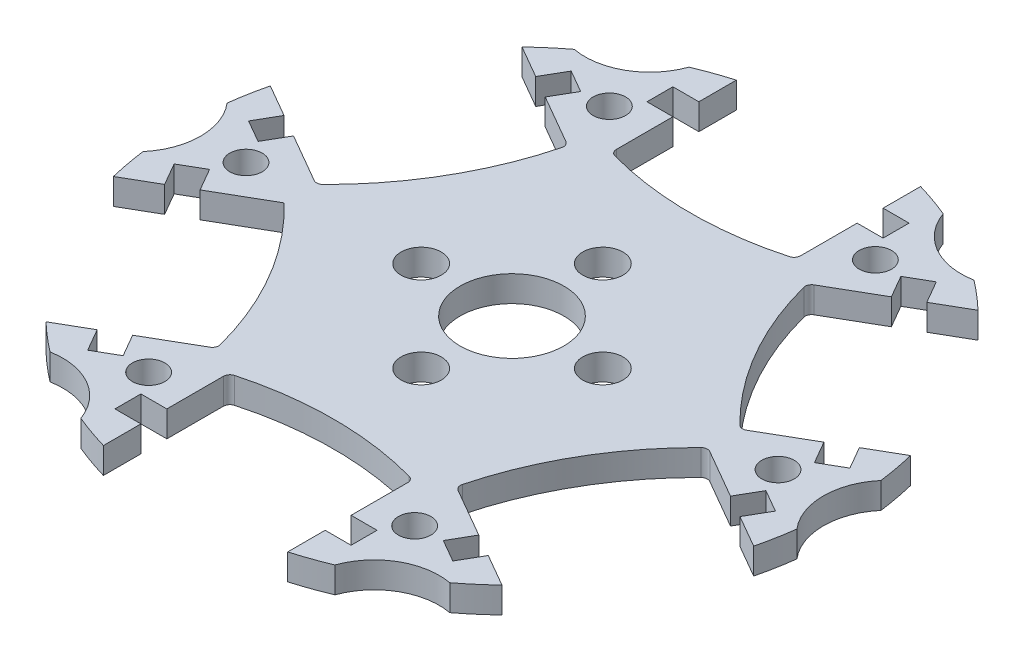
SolidWorks part; units mm, degrees
material "Hexcel AS4C (3000 丝)"
ref_plane "前视基准面" through (0, 0, 0) normal (0, 0, 1) x (1, 0, 0)
ref_plane "上视基准面" through (0, 0, 0) normal (0, 1, 0) x (1, 0, 0)
ref_plane "右视基准面" through (0, 0, 0) normal (1, 0, 0) x (0, 0, -1)
sketch "草图1" plane through (0, 0, 0) normal (0, 1, 0) x (1, 0, 0)
  circle A0 centre (0, 0) radius 25.4
  circle A1 centre (0, 0) radius 4
  dimension "D1" = 50.8
  dimension "D2" = 8
extrude "凸台-拉伸1" add sketch "草图1" along normal blind 2
sketch "草图2" plane through (0, 2, 0) normal (0, 1, 0) x (1, 0, 0)
  line L0 (0, 25.4) -> (0, -24.9458) construction
  line L1 (-7.1, 24.3875) -> (-7.1, 14.7625)
  line L2 (7.1, 24.3875) -> (7.1, 14.7625)
  line L3 (17.5702, 18.3425) -> (9.2347, 13.53)
  line L4 (7.1, 25.4) -> (7.1, -24.9458) construction
  line L5 (-7.1, 25.4) -> (-7.1, -24.9458) construction
  line L6 (24.6702, 6.045) -> (16.3347, 1.2325)
  line L7 (24.6702, -6.045) -> (16.3347, -1.2325)
  line L8 (17.5702, -18.3425) -> (9.2347, -13.53)
  line L9 (7.1, -24.3875) -> (7.1, -14.7625)
  line L10 (-7.1, -24.3875) -> (-7.1, -14.7625)
  line L11 (-17.5702, -18.3425) -> (-9.2347, -13.53)
  line L12 (-24.6702, -6.045) -> (-16.3347, -1.2325)
  line L13 (-24.6702, 6.045) -> (-16.3347, 1.2325)
  line L14 (-17.5702, 18.3425) -> (-9.2347, 13.53)
  circle A0 centre (0, 0) radius 25.4 construction
  arc A1 (7.1, 24.3875) -> (-7.1, 24.3875) centre (0, 0) ccw
  arc A2 (-7.1, 14.7625) -> (7.1, 14.7625) centre (0, 39.15) ccw
  arc A3 (24.6702, 6.045) -> (17.5702, 18.3425) centre (0, 0) ccw
  arc A4 (9.2347, 13.53) -> (16.3347, 1.2325) centre (33.9049, 19.575) ccw
  arc A5 (17.5702, -18.3425) -> (24.6702, -6.045) centre (0, 0) ccw
  arc A6 (16.3347, -1.2325) -> (9.2347, -13.53) centre (33.9049, -19.575) ccw
  arc A7 (-7.1, -24.3875) -> (7.1, -24.3875) centre (0, 0) ccw
  arc A8 (7.1, -14.7625) -> (-7.1, -14.7625) centre (0, -39.15) ccw
  arc A9 (-24.6702, -6.045) -> (-17.5702, -18.3425) centre (0, 0) ccw
  arc A10 (-9.2347, -13.53) -> (-16.3347, -1.2325) centre (-33.9049, -19.575) ccw
  arc A11 (-17.5702, 18.3425) -> (-24.6702, 6.045) centre (0, 0) ccw
  arc A12 (-16.3347, 1.2325) -> (-9.2347, 13.53) centre (-33.9049, 19.575) ccw
  point P43 (0, 0)
  dimension "D3" = 50.8
  dimension "D4" = 39.15
  dimension "D1" = 7.1
  dimension "D2" = 7.1
  dimension "D5" = 6
extrude "切除-拉伸1" cut sketch "草图2" against normal through all
sketch "草图3" plane through (0, 2, 0) normal (0, 1, 0) x (1, 0, 0)
  line L0 (-12.7, 21.997) -> (12.7, -21.997) construction
  circle A0 centre (0, 0) radius 20.5 construction
  arc A1 (-7.1, 24.3875) -> (-17.5702, 18.3425) centre (0, 0) ccw construction
  arc A2 (7.1, -24.3875) -> (17.5702, -18.3425) centre (0, 0) ccw construction
  circle A3 centre (-10.25, 17.7535) radius 1.25
  circle A4 centre (10.25, 17.7535) radius 1.25
  circle A5 centre (20.5, 0) radius 1.25
  circle A6 centre (10.25, -17.7535) radius 1.25
  circle A7 centre (-10.25, -17.7535) radius 1.25
  circle A8 centre (-20.5, 0) radius 1.25
  circle A9 centre (-29, 0) radius 5
  circle A10 centre (-14.5, 25.1147) radius 5
  circle A11 centre (14.5, 25.1147) radius 5
  circle A12 centre (29, 0) radius 5
  circle A13 centre (14.5, -25.1147) radius 5
  circle A14 centre (-14.5, -25.1147) radius 5
  point P25 (0, 0)
  point P38 (0, 0)
  dimension "D1" = 41
  dimension "D2" = 2.5
  dimension "D4" = 10
  dimension "D5" = 29
  dimension "D3" = 6
  dimension "D6" = 6
extrude "切除-拉伸2" cut sketch "草图3" against normal through all
fillet "圆角1" radius 0.5 11 edges at (-7.1, 1, -14.7625) (7.1, 1, -14.7625) (9.2347, 1, -13.53) (16.3347, 1, -1.2325) (16.3347, 1, 1.2325) (9.2347, 1, 13.53) (7.1, 1, 14.7625) (-7.1, 1, 14.7625) (-9.2347, 1, 13.53) (-16.3347, 1, -1.2325) (-9.2347, 1, -13.53)
sketch "草图4" plane through (0, 2, 0) normal (0, 1, 0) x (1, 0, 0)
  circle A0 centre (0, 0) radius 7 construction
  circle A1 centre (-7, 0) radius 1.55
  circle A2 centre (0, 7) radius 1.55
  circle A3 centre (7, 0) radius 1.55
  circle A4 centre (0, -7) radius 1.55
  point P14 (0, 0)
  dimension "D1" = 3.1
  dimension "D2" = 14
  dimension "D3" = 4
extrude "切除-拉伸3" cut sketch "草图4" against normal through all
sketch "草图5" plane through (0, 2, 0) normal (0, 1, 0) x (1, 0, 0)
  line L0 (-11.9085, -6.8754) -> (11.9084, 6.8753) construction
  line L1 (-17.5702, -18.3425) -> (-9.5622, -13.7191) construction
  line L2 (-16.3347, -1.2325) -> (-24.6702, -6.045) construction
  line L3 (-12.3375, -17.6308) -> (-21.4375, -1.8692)
  line L4 (-12, 20.7846) -> (12, -20.7846) construction
  line L5 (21.4375, 1.8692) -> (12.3375, 17.6308) construction
  line L6 (-14.0695, -18.6308) -> (-23.1695, -2.8692)
  line L7 (-14.0695, -18.6308) -> (-12.3375, -17.6308)
  line L8 (-23.1695, -2.8692) -> (-21.4375, -1.8692)
  line L9 (-14.0695, 18.6308) -> (-12.3375, 17.6308)
  line L10 (-21.4375, 1.8692) -> (-12.3375, 17.6308)
  line L11 (-23.1695, 2.8692) -> (-21.4375, 1.8692)
  line L12 (-23.1695, 2.8692) -> (-14.0695, 18.6308)
  line L13 (9.1, 21.5) -> (9.1, 19.5)
  line L14 (-9.1, 19.5) -> (9.1, 19.5)
  line L15 (-9.1, 21.5) -> (-9.1, 19.5)
  line L16 (-9.1, 21.5) -> (9.1, 21.5)
  line L17 (23.1695, 2.8692) -> (21.4375, 1.8692)
  line L18 (12.3375, 17.6308) -> (21.4375, 1.8692)
  line L19 (14.0695, 18.6308) -> (12.3375, 17.6308)
  line L20 (14.0695, 18.6308) -> (23.1695, 2.8692)
  line L21 (14.0695, -18.6308) -> (12.3375, -17.6308)
  line L22 (21.4375, -1.8692) -> (12.3375, -17.6308)
  line L23 (23.1695, -2.8692) -> (21.4375, -1.8692)
  line L24 (23.1695, -2.8692) -> (14.0695, -18.6308)
  line L25 (-9.1, -21.5) -> (-9.1, -19.5)
  line L26 (9.1, -19.5) -> (-9.1, -19.5)
  line L27 (9.1, -21.5) -> (9.1, -19.5)
  line L28 (9.1, -21.5) -> (-9.1, -21.5)
  arc A2 (-15.4028, 20.1969) -> (-9.7897, 23.4376) centre (-14.5, 25.1147) ccw construction
  arc A3 (15.4028, -20.1969) -> (9.7897, -23.4376) centre (14.5, -25.1147) ccw construction
  point P43 (0, 0)
  dimension "D1" = 39
  dimension "D3" = 18.2
  dimension "D2" = 2
  dimension "D4" = 6
extrude "切除-拉伸4" cut sketch "草图5" against normal blind 2
